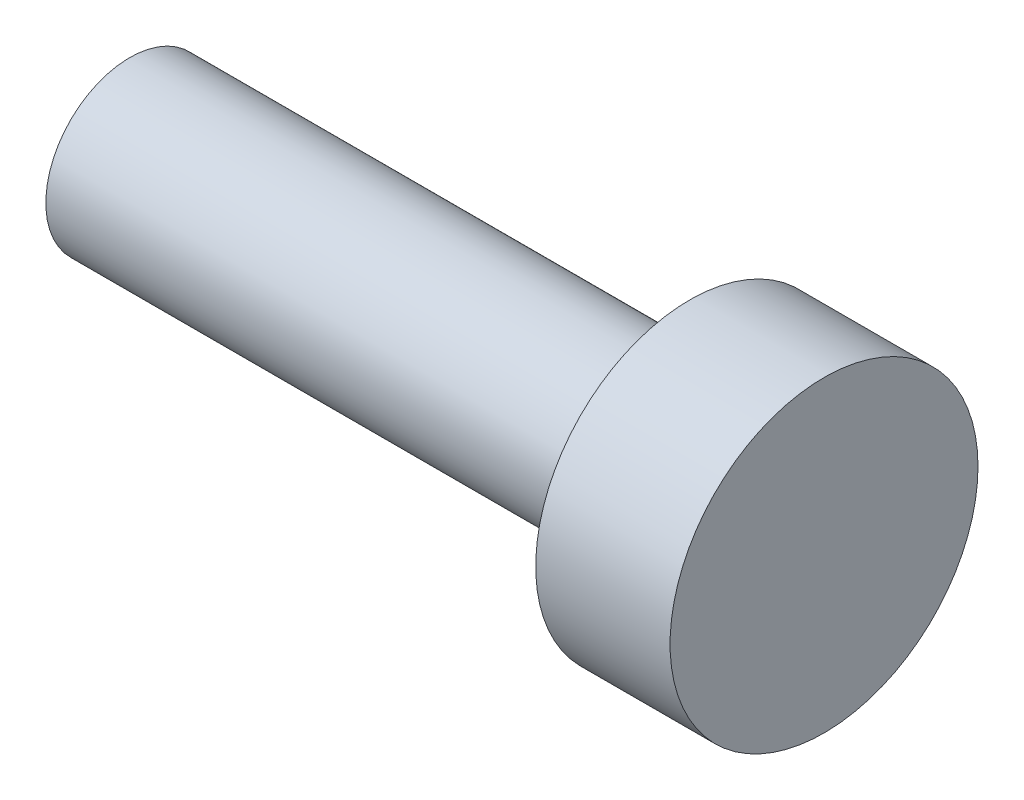
SolidWorks part; units mm, degrees
other "Preload Carriage Clamp M3 Bolt"
ref_plane "Front Plane" through (0, 0, 0) normal (0, 0, 1) x (1, 0, 0)
ref_plane "Top Plane" through (0, 0, 0) normal (0, 1, 0) x (1, 0, 0)
ref_plane "Right Plane" through (0, 0, 0) normal (1, 0, 0) x (0, 0, -1)
sketch3d "M3 clamp shank sketch datum points"
  point P0 (44.7083, -19, -12)
  point P1 (44.7083, -9, -12)
  point P2 (44.7083, -19, -2)
ref_plane "M3 clamp shank sketch plane" through (44.7083, 0, 0) normal (1, 0, 0) x (0, 0, -1)
sketch "M3 clamp shank sketch" plane through (44.7083, 0, 0) normal (1, 0, 0) x (0, 0, -1)
  circle A0 centre (12, -19) radius 1.5
extrude "M3 clamp shank" add sketch "M3 clamp shank sketch" along normal blind 10 separate body
sketch3d "Clamp screw head sketch datum points"
  point P0 (54.7083, -19, -12)
  point P1 (54.7083, -9, -12)
  point P2 (54.7083, -19, -2)
ref_plane "Clamp screw head sketch plane" through (54.7083, 0, 0) normal (1, 0, 0) x (0, 0, -1)
sketch "Clamp screw head sketch" plane through (54.7083, 0, 0) normal (1, 0, 0) x (0, 0, -1)
  circle A0 centre (12, -19) radius 2.75
extrude "Clamp screw head" add sketch "Clamp screw head sketch" along normal blind 2.4
